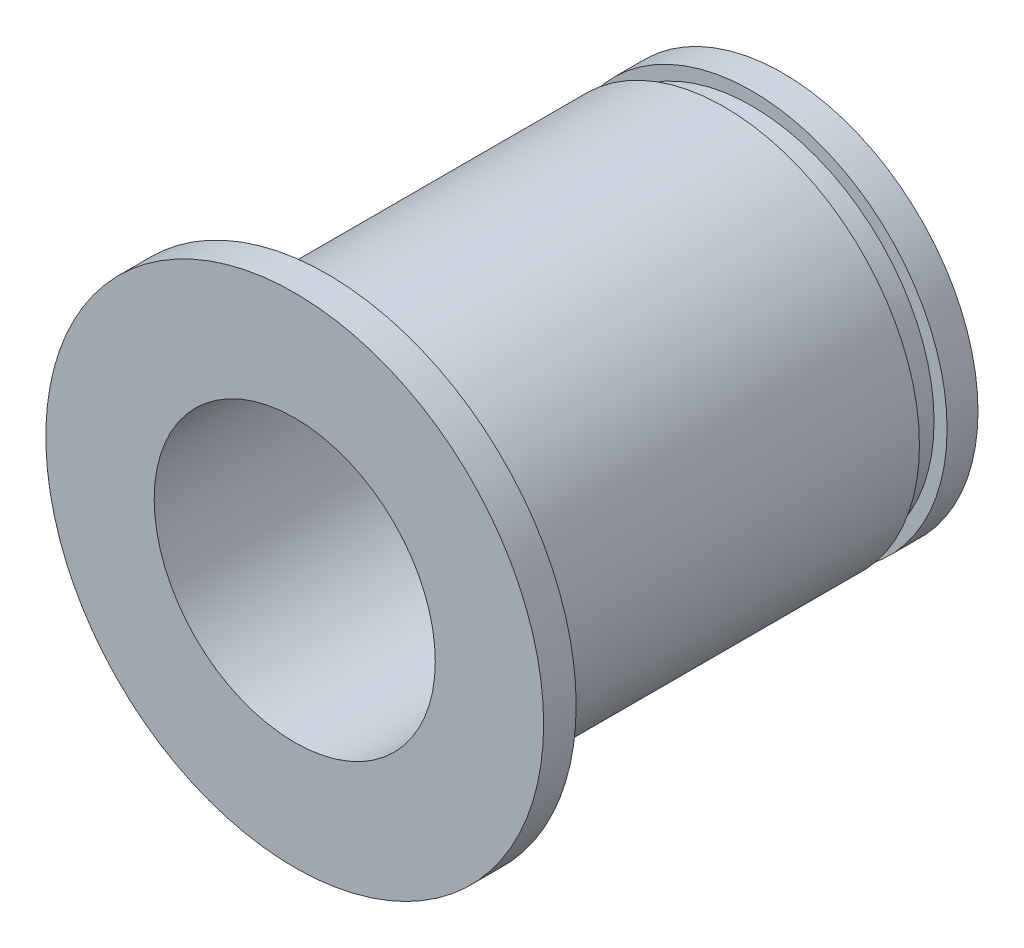
SolidWorks part; units mm, degrees
ref_plane "Front Plane" through (0, 0, 0) normal (0, 0, 1) x (1, 0, 0)
ref_plane "Top Plane" through (0, 0, 0) normal (0, 1, 0) x (1, 0, 0)
ref_plane "Right Plane" through (0, 0, 0) normal (1, 0, 0) x (0, 0, -1)
sketch "S01 - Ground guide bore and body" plane through (0, 0, 0) normal (0, 0, 1) x (1, 0, 0)
  circle A0 centre (0, 0) radius 6
  circle A1 centre (0, 0) radius 4.32
  dimension "D1" = 8.64
  dimension "D2" = 12
extrude "01 - Ground guide bore and body" add sketch "S01 - Ground guide bore and body" along normal blind 14 from offset 2
sketch "S02 - Outboard flange" plane through (0, 0, 0) normal (0, 0, 1) x (1, 0, 0)
  circle A0 centre (0, 0) radius 7.65
  circle A1 centre (0, 0) radius 4.32
  dimension "D1" = 8.64
  dimension "D2" = 15.3
extrude "02 - Outboard flange" add sketch "S02 - Outboard flange" along normal blind 1 from offset 12
sketch "S03 - External retaining ring groove" plane through (0, 0, 0) normal (0, 0, 1) x (1, 0, 0)
  circle A0 centre (0, 0) radius 6.1
  circle A1 centre (0, 0) radius 5.6
  dimension "D1" = 11.2
  dimension "D2" = 12.2
extrude "03 - External retaining ring groove" cut sketch "S03 - External retaining ring groove" along normal blind 0.85 from offset 1.05
